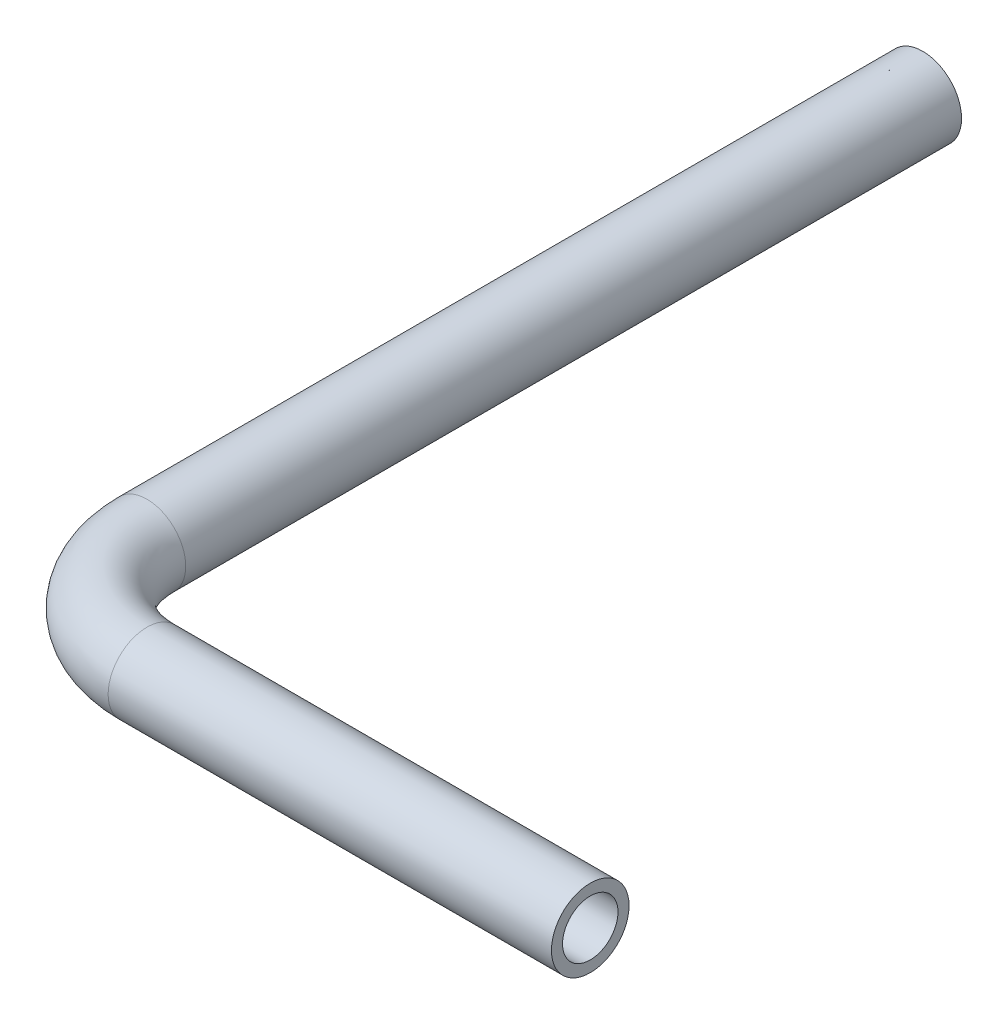
SolidWorks part; units mm, degrees
ref_plane "前视基准面" through (0, 0, 0) normal (0, 0, 1) x (1, 0, 0)
ref_plane "上视基准面" through (0, 0, 0) normal (0, 1, 0) x (1, 0, 0)
ref_plane "右视基准面" through (0, 0, 0) normal (1, 0, 0) x (0, 0, -1)
sketch "草图1" plane through (0, 0, 0) normal (1, 0, 0) x (0, 0, -1)
  circle A0 centre (0, 0) radius 12.5
  circle A1 centre (0, 0) radius 17.5
sketch "草图2" plane through (0, 0, 0) normal (0, 1, 0) x (1, 0, 0)
  line L0 (0, 0) -> (-450, 0)
  line L1 (-500, 50) -> (-500, 400)
  arc A0 (-450, 0) -> (-500, 50) centre (-450, 50) cw
  dimension "D1" = 50
sweep "扫描1" add profiles "草图1" path "草图2"
ref_plane "基准面1" through (-250, 0, 0) normal (1, 0, 0) x (0, 0, -1)
sketch "草图3" plane through (-250, 0, 0) normal (1, 0, 0) x (0, 0, -1)
  circle A0 centre (0, 0) radius 12.5
  circle A1 centre (0, 0) radius 17.5
ref_plane "基准面2" through (-150, 0, 0) normal (1, 0, 0) x (0, 0, -1)
extrude "切除-拉伸3" cut sketch "草图3" along normal up to next
